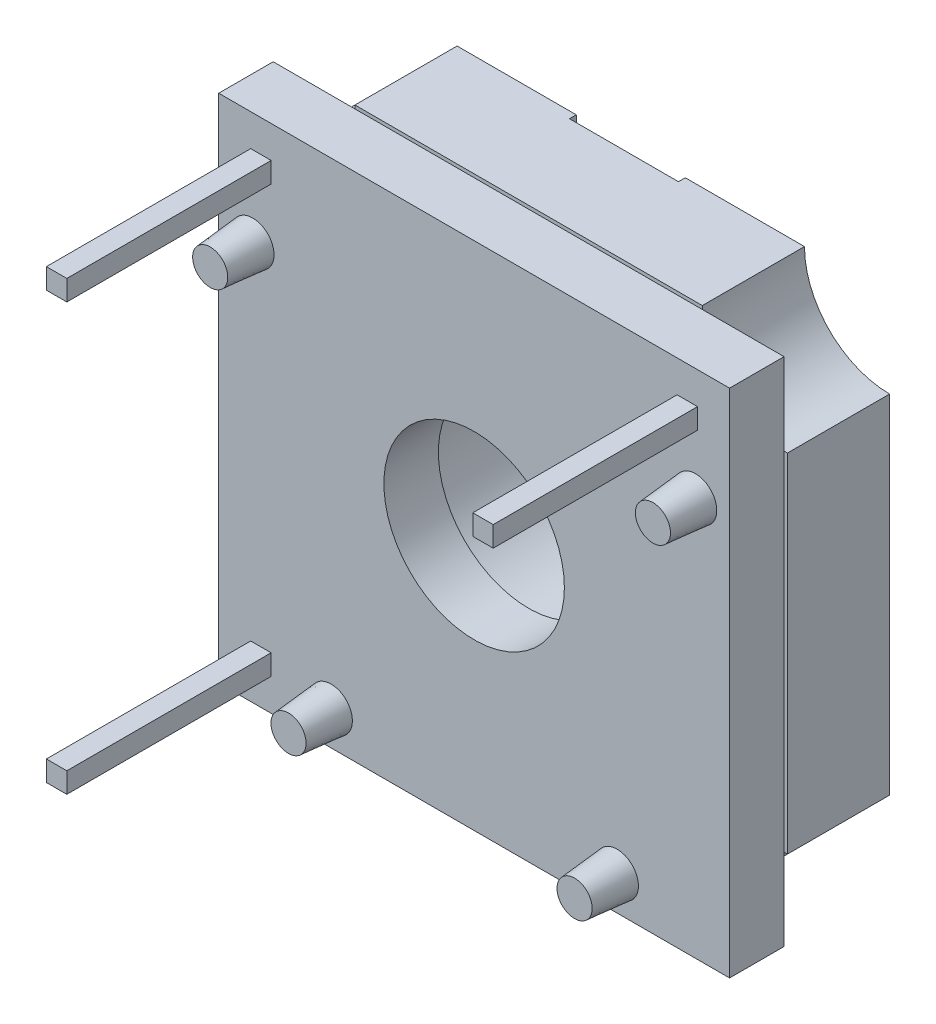
SolidWorks part; units mm, degrees
ref_plane "Front Plane" through (0, 0, 0) normal (0, 0, 1) x (1, 0, 0)
ref_plane "Top Plane" through (0, 0, 0) normal (0, 1, 0) x (1, 0, 0)
ref_plane "Right Plane" through (0, 0, 0) normal (1, 0, 0) x (0, 0, -1)
sketch "Sketch1" plane through (0, 0, 0) normal (0, 0, 1) x (1, 0, 0)
  line L0 (0, 0) -> (0, 8.9788) construction
  line L1 (-5.1, 7.6) -> (5.1, 7.6)
  line L2 (-7.6, 5.1) -> (-7.6, -5.1)
  line L3 (-5.1, -7.6) -> (5.1, -7.6)
  line L4 (7.6, 5.1) -> (7.6, -5.1)
  line L5 (0, 0) -> (-5.231, 0) construction
  circle A0 centre (0, 0) radius 3.2
  arc A1 (5.1, -7.6) -> (7.6, -5.1) centre (7.6, -7.6) cw
  arc A2 (5.1, 7.6) -> (7.6, 5.1) centre (7.6, 7.6) ccw
  arc A3 (-5.1, -7.6) -> (-7.6, -5.1) centre (-7.6, -7.6) ccw
  arc A4 (-5.1, 7.6) -> (-7.6, 5.1) centre (-7.6, 7.6) cw
  dimension "D5" = 6.4
  dimension "D1" = 15.2
  dimension "D2" = 15.2
  dimension "D3" = 7.6
  dimension "D4" = 7.6
  dimension "D6" = 2.5
extrude "Extrude1" add sketch "Sketch1" along normal blind 3
sketch "Sketch2" plane through (0, 0, 3) normal (0, 0, 1) x (1, 0, 0)
  line L1 (-7.5, 7.5) -> (7.5, 7.5)
  line L2 (-7.5, 7.5) -> (-7.5, -7.5)
  line L3 (-7.5, -7.5) -> (7.5, -7.5)
  line L4 (7.5, 7.5) -> (7.5, -7.5)
  circle A0 centre (0, 0) radius 2.65
  dimension "D5" = 5.3
  dimension "D1" = 7.5
  dimension "D2" = 7.5
  dimension "D3" = 15
  dimension "D4" = 15
extrude "Extrude2" add sketch "Sketch2" along normal blind 1.6
sketch "Sketch3" plane through (0, 0, 4.6) normal (0, 0, 1) x (1, 0, 0)
  line L0 (0, 0) -> (0, 8.7587) construction
  line L1 (-6.56, 6.56) -> (-5.96, 6.56)
  line L2 (-6.56, 6.56) -> (-6.56, 5.96)
  line L3 (-6.56, 5.96) -> (-5.96, 5.96)
  line L4 (-5.96, 6.56) -> (-5.96, 5.96)
  line L5 (0, 0) -> (8.6075, 0) construction
  line L6 (5.96, 6.56) -> (5.96, 5.96)
  line L7 (6.56, 5.96) -> (5.96, 5.96)
  line L8 (6.56, 6.56) -> (6.56, 5.96)
  line L9 (6.56, 6.56) -> (5.96, 6.56)
  line L10 (-5.96, -6.56) -> (-5.96, -5.96)
  line L11 (-6.56, -5.96) -> (-5.96, -5.96)
  line L12 (-6.56, -6.56) -> (-6.56, -5.96)
  line L13 (-6.56, -6.56) -> (-5.96, -6.56)
  dimension "D1" = 0.6
  dimension "D2" = 0.6
  dimension "D3" = 6.56
  dimension "D4" = 6.56
extrude "Extrude3" add sketch "Sketch3" along normal blind 6
sketch "Sketch4" plane through (0, 0, 4.6) normal (0, 0, 1) x (1, 0, 0)
  line L0 (0, 0) -> (0, -8.8892) construction
  circle A0 centre (-4.2, -6.5) radius 0.625
  circle A1 centre (4.2, -6.5) radius 0.625
  circle A2 centre (-6.5, 4.2) radius 0.625
  circle A3 centre (6.5, 4.2) radius 0.625
  dimension "D3" = 1.25
  dimension "D1" = 4.2
  dimension "D2" = 6.5
  dimension "D4" = 4.2
  dimension "D5" = 6.5
extrude "Extrude4" add sketch "Sketch4" along normal blind 1.25 draft 5
sketch "Sketch5" plane through (0, 0, 0) normal (0, 0, -1) x (-1, 0, 0)
  line L0 (-5.1, 7.6) -> (5.1, 7.6) construction
  line L1 (-1.6, 7.6) -> (1.6, 7.6)
  line L2 (-1.6, 7.6) -> (-1.6, 7.1)
  line L3 (-1.6, 7.1) -> (-0.6, 7.1)
  line L4 (0.6, 7.1) -> (0, 6.5)
  line L5 (-0.6, 7.1) -> (0, 6.5)
  line L6 (1.6, 7.1) -> (0.6, 7.1)
  line L7 (-7.6, -5.1) -> (-7.6, 5.1) construction
  line L8 (0, 0) -> (0, 9.7134) construction
  line L9 (1.6, 7.6) -> (1.6, 7.1)
  point P15 (0, 7.6)
  dimension "D1" = 6
  dimension "D2" = 1
  dimension "D3" = 135
  dimension "D4" = 0.5
extrude "Cut-Extrude1" cut sketch "Sketch5" against normal blind 0.2
